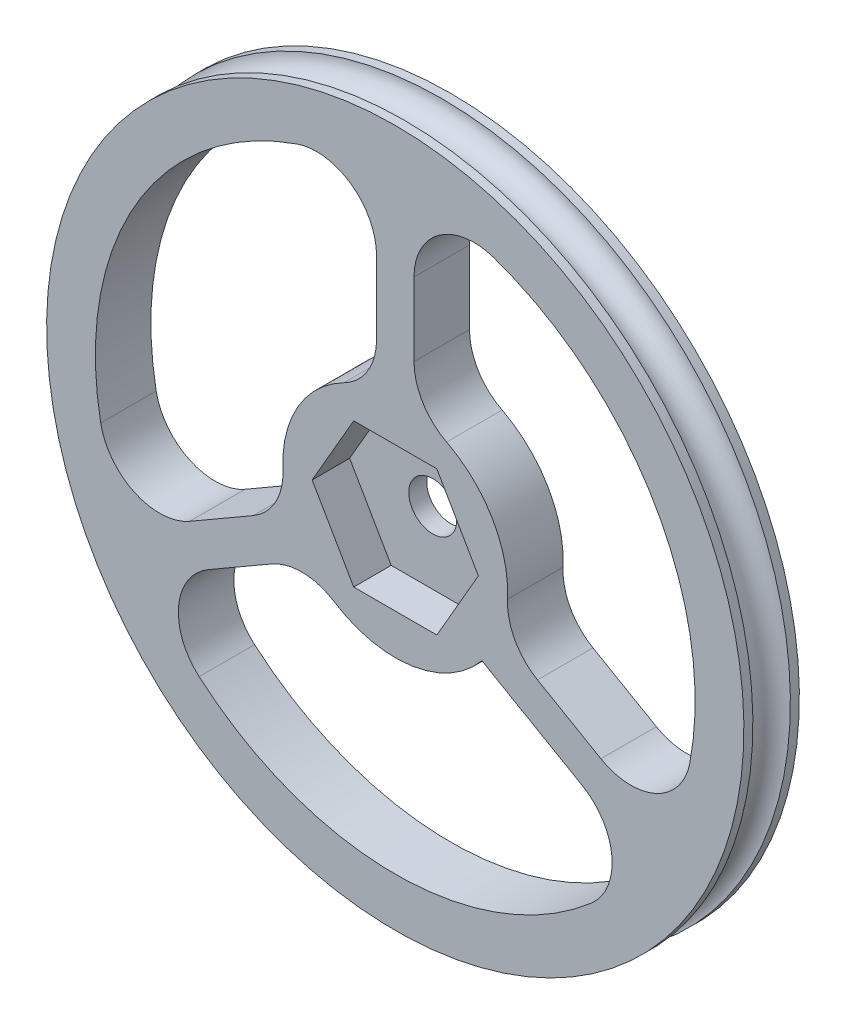
SolidWorks part; units mm, degrees
ref_plane "Front Plane" through (0, 0, 0) normal (0, 0, 1) x (1, 0, 0)
ref_plane "Top Plane" through (0, 0, 0) normal (0, 1, 0) x (1, 0, 0)
ref_plane "Right Plane" through (0, 0, 0) normal (1, 0, 0) x (0, 0, -1)
sketch "Sketch1" plane through (0, 0, 0) normal (0, 0, 1) x (1, 0, 0)
  line L0 (0, 0) -> (0, 12.7) construction
  line L1 (0, 0) -> (0, 25.4) construction
  line L2 (-1.5875, 25.3503) -> (-1.5875, 9.3918)
  line L3 (-1.5875, 9.3918) -> (1.5875, 9.3918) construction
  line L4 (1.5875, 9.3918) -> (1.5875, 25.3503)
  line L5 (22.7478, -11.3004) -> (8.9273, -3.3211)
  line L6 (7.3398, -6.0707) -> (21.1603, -14.05)
  line L7 (-21.1603, -14.05) -> (-7.3398, -6.0707)
  line L8 (-8.9273, -3.3211) -> (-22.7478, -11.3004)
  circle A0 centre (0, 0) radius 25.4
  circle A1 centre (0, 0) radius 9.525
  point P32 (0, 0)
  dimension "D1" = 50.8
  dimension "D4" = 3.175
  dimension "D3" = 19.05
  dimension "D2" = 12.7
  dimension "D5" = 3
sketch "Sketch2" plane through (0, 0, 0) normal (0, 0, 1) x (1, 0, 0)
  line L1 (7.0391, 0) -> (3.5195, 6.096)
  line L2 (3.5195, 6.096) -> (-3.5195, 6.096)
  line L3 (-3.5195, 6.096) -> (-7.0391, 0)
  line L4 (-7.0391, 0) -> (-3.5195, -6.096)
  line L5 (-3.5195, -6.096) -> (3.5195, -6.096)
  line L6 (3.5195, -6.096) -> (7.0391, 0)
  circle A0 centre (0, 0) radius 6.096 construction
  dimension "D1" = 12.192
sketch "Sketch3" plane through (0, 0, 0) normal (1, 0, 0) x (0, 0, -1)
  line L0 (0.762, 29.5275) -> (0.762, 27.94) construction
  line L1 (0.762, 27.94) -> (3.937, 27.94) construction
  line L2 (3.937, 27.94) -> (3.937, 29.5275) construction
  line L4 (0, 25.4) -> (0, 29.5275)
  line L5 (0, 29.5275) -> (0.762, 29.5275)
  line L6 (3.937, 29.5275) -> (4.699, 29.5275)
  line L7 (4.699, 29.5275) -> (4.699, 25.4)
  line L10 (0, 25.4) -> (4.699, 25.4)
  arc A0 (0.762, 29.5275) -> (3.937, 29.5275) centre (2.3495, 29.5275) ccw
  dimension "D1" = 1.5875
  dimension "D2" = 3.175
  dimension "D3" = 0.762
  dimension "D4" = 2.54
extrude "Boss-Extrude1" add sketch "Sketch1" against normal blind 4.699 contours A1 L4 A0 L2 | A1 | A1 L6 A0 L5 | A1 L8 A0 L7
sketch "Sketch4" plane through (0, 0, 0) normal (0, 0, 1) x (1, 0, 0)
  circle A0 centre (0, 0) radius 25.4
sweep "Sweep1" add profiles "Sketch3" path "Sketch4"
extrude "Cut-Extrude1" cut sketch "Sketch2" against normal blind 3.175
sketch "Sketch5" plane through (0, 0, 0) normal (0, 0, 1) x (1, 0, 0)
  circle A0 centre (0, 0) radius 2.032
  dimension "D1" = 4.064
extrude "Cut-Extrude2" cut sketch "Sketch5" against normal through all
fillet "Fillet1" radius 5.08 11 edges at (-22.7478, -11.3004, -2.3495) (-21.1603, -14.05, -2.3495) (-7.3398, -6.0707, -2.3495) (-1.5875, 25.3503, -2.3495) (21.1603, -14.05, -2.3495) (-1.5875, 9.3918, -2.3495) (-8.9273, -3.3211, -2.3495) (22.7478, -11.3004, -2.3495) (1.5875, 25.3503, -2.3495) (8.9273, -3.3211, -2.3495) (1.5875, 9.3918, -2.3495)
